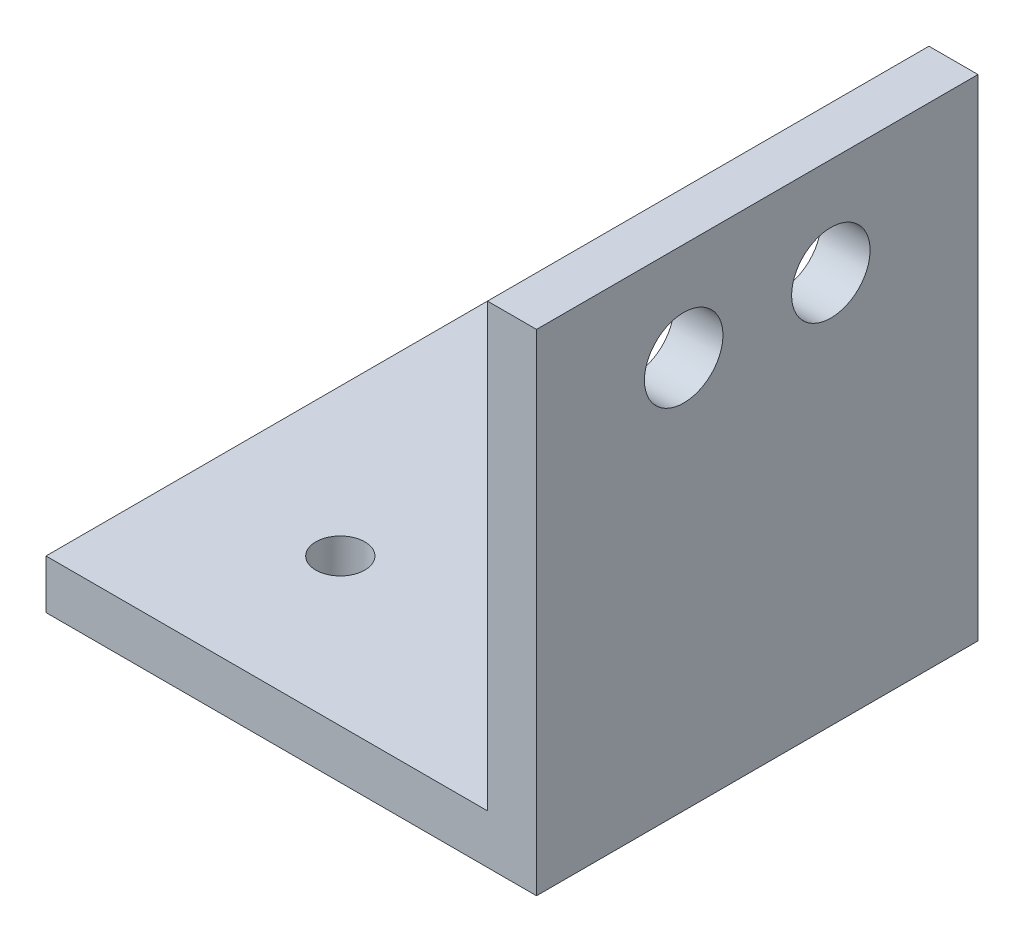
SolidWorks part; units mm, degrees
ref_plane "Front Plane" through (0, 0, 0) normal (0, 0, 1) x (1, 0, 0)
ref_plane "Top Plane" through (0, 0, 0) normal (0, 1, 0) x (1, 0, 0)
ref_plane "Right Plane" through (0, 0, 0) normal (1, 0, 0) x (0, 0, -1)
sketch "Sketch1" plane through (0, 0, 0) normal (0, 0, 1) x (1, 0, 0)
  line L0 (0, 0) -> (0, 50)
  line L1 (0, 50) -> (-5, 50)
  line L2 (-5, 50) -> (-5, 5)
  line L3 (-5, 5) -> (-50, 5)
  line L4 (-50, 5) -> (-50, 0)
  line L5 (-50, 0) -> (0, 0)
  dimension "D1" = 5
  dimension "D2" = 5
  dimension "D3" = 50
  dimension "D4" = 50
extrude "Boss-Extrude1" add sketch "Sketch1" along normal blind 45
sketch "Sketch2" plane through (-5, 0, 0) normal (-1, 0, 0) x (0, 0, 1)
  line L0 (45, 50) -> (0, 50) construction
  line L1 (0, 50) -> (0, 5) construction
  line L2 (45, 50) -> (45, 5) construction
  circle A0 centre (15, 40) radius 4
  circle A1 centre (30, 40) radius 4
  dimension "D1" = 8
  dimension "D4" = 8
  dimension "D2" = 10
  dimension "D3" = 15
  dimension "D5" = 10
  dimension "D6" = 15
extrude "Cut-Extrude1" cut sketch "Sketch2" against normal through all
sketch "Sketch3" plane through (0, 0, 0) normal (0, 1, 0) x (1, 0, 0)
  line L0 (-50, -45) -> (-50, 0) construction
  line L1 (-5, -45) -> (-50, -45) construction
  line L2 (-5, 0) -> (-50, 0) construction
  circle A0 centre (-35, -30) radius 2.5
  circle A1 centre (-20, -15) radius 2.5
  dimension "D1" = 15
  dimension "D5" = 5
  dimension "D6" = 5
  dimension "D2" = 15
  dimension "D3" = 15
  dimension "D4" = 30
extrude "Cut-Extrude3" cut sketch "Sketch3" along normal through all
